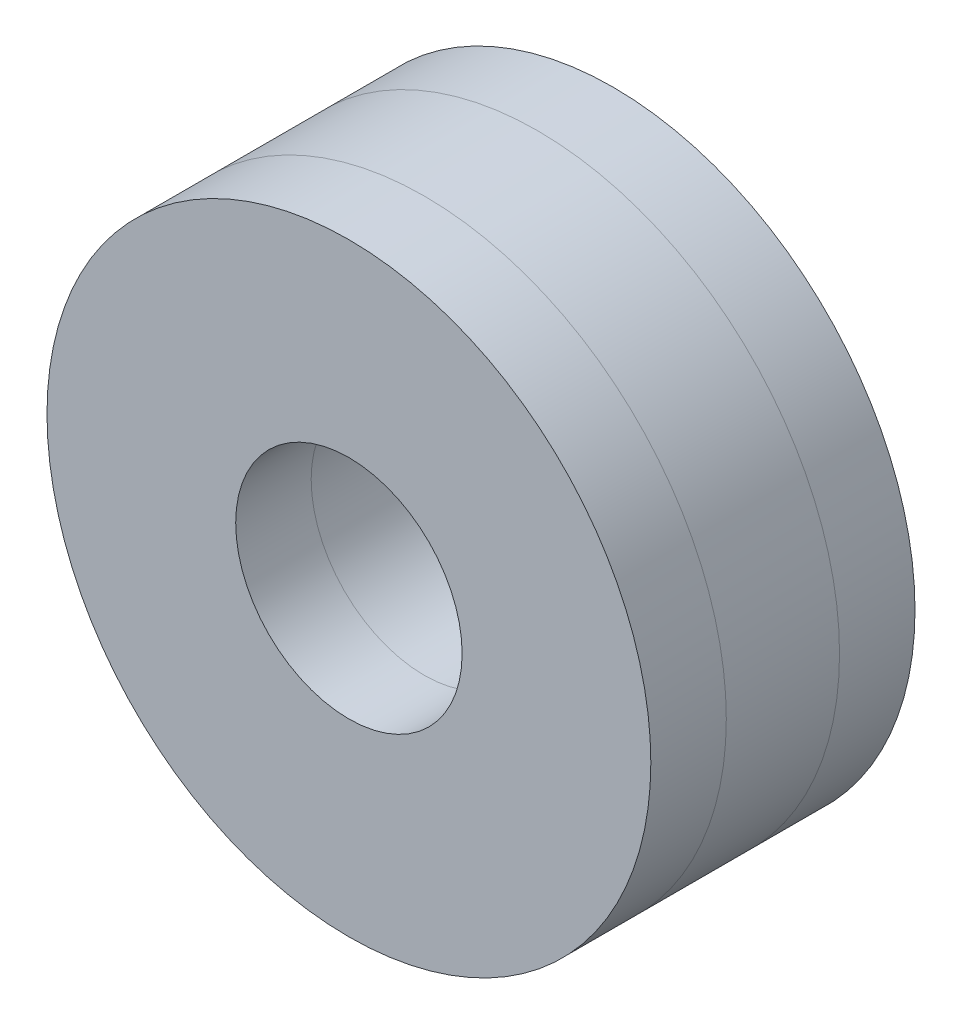
SolidWorks part; units mm, degrees
ref_plane "Alzado" through (0, 0, 0) normal (0, 0, 1) x (1, 0, 0)
ref_plane "Planta" through (0, 0, 0) normal (0, 1, 0) x (1, 0, 0)
ref_plane "Vista lateral" through (0, 0, 0) normal (1, 0, 0) x (0, 0, -1)
sketch "Croquis1" plane through (0, 0, 0) normal (0, 0, 1) x (1, 0, 0)
  circle A0 centre (0, 0) radius 4
  circle A1 centre (0, 0) radius 1.5
  dimension "D1" = 8
  dimension "D2" = 3
extrude "Saliente-Extruir1" add sketch "Croquis1" along normal blind 1
sketch "Croquis2" plane through (0, 0, 1) normal (0, 0, 1) x (1, 0, 0)
  circle A0 centre (0, 0) radius 4
  circle A1 centre (0, 0) radius 1.5
extrude "Saliente-Extruir2" add sketch "Croquis2" along normal blind 1.5 separate body
sketch "Croquis3" plane through (0, 0, 2.5) normal (0, 0, 1) x (1, 0, 0)
  circle A0 centre (0, 0) radius 1.5
  circle A1 centre (0, 0) radius 4
extrude "Saliente-Extruir3" add sketch "Croquis3" along normal blind 1 separate body
